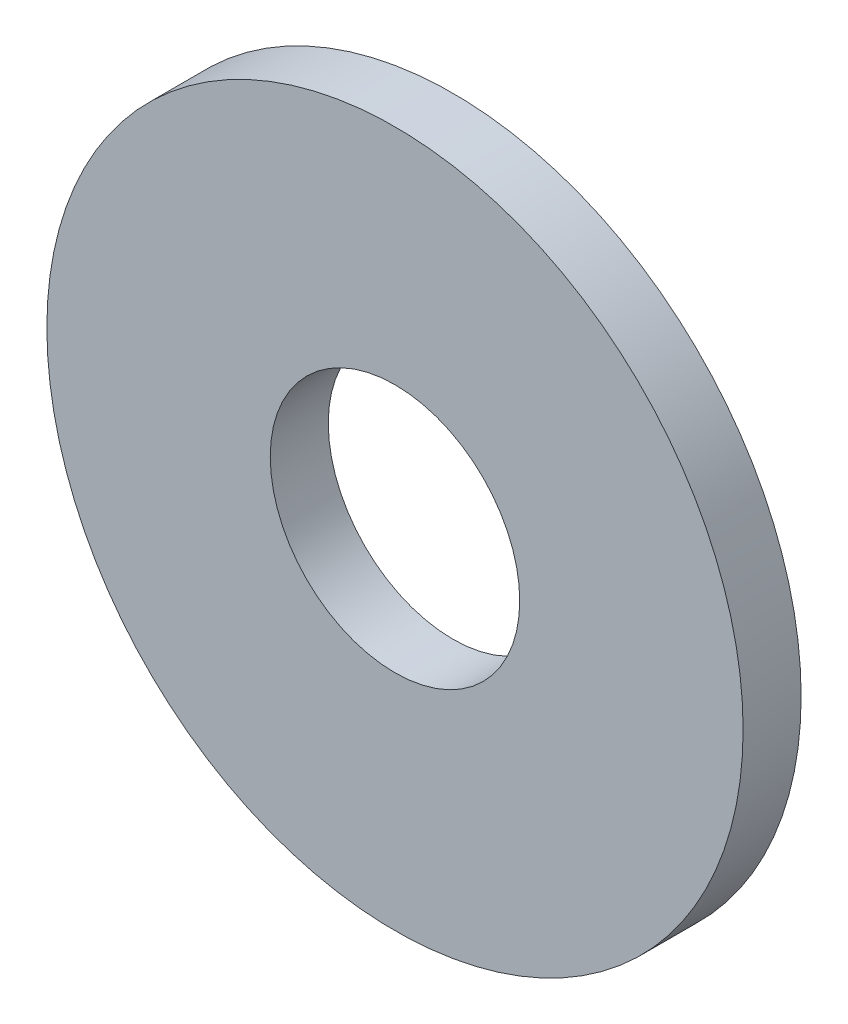
SolidWorks part; units mm, degrees
ref_plane "Front Plane" through (0, 0, 0) normal (0, 0, 1) x (1, 0, 0)
ref_plane "Top Plane" through (0, 0, 0) normal (0, 1, 0) x (1, 0, 0)
ref_plane "Right Plane" through (0, 0, 0) normal (1, 0, 0) x (0, 0, -1)
sketch "Sketch1" plane through (0, 0, 0) normal (1, 0, 0) x (0, 0, -1)
  line L0 (0, -6) -> (0, 6) construction
  line L1 (0, -2.15) -> (0, 2.15) construction
  line L2 (-0.5, 0) -> (0.5, 0) construction
  point P4 (0, 0)
  point P8 (0, 0)
  point P11 (0, 0)
sketch "Sketch2" plane through (0, 0, 0) normal (0, 0, 1) x (1, 0, 0)
  circle A0 centre (0, 0) radius 6
  circle A1 centre (0, 0) radius 2.15
extrude "Boss-Extrude1" add sketch "Sketch2" along normal mid plane 1
equation "\"D1@Boss-Extrude1\" = \"Thickness@Sketch1\""
